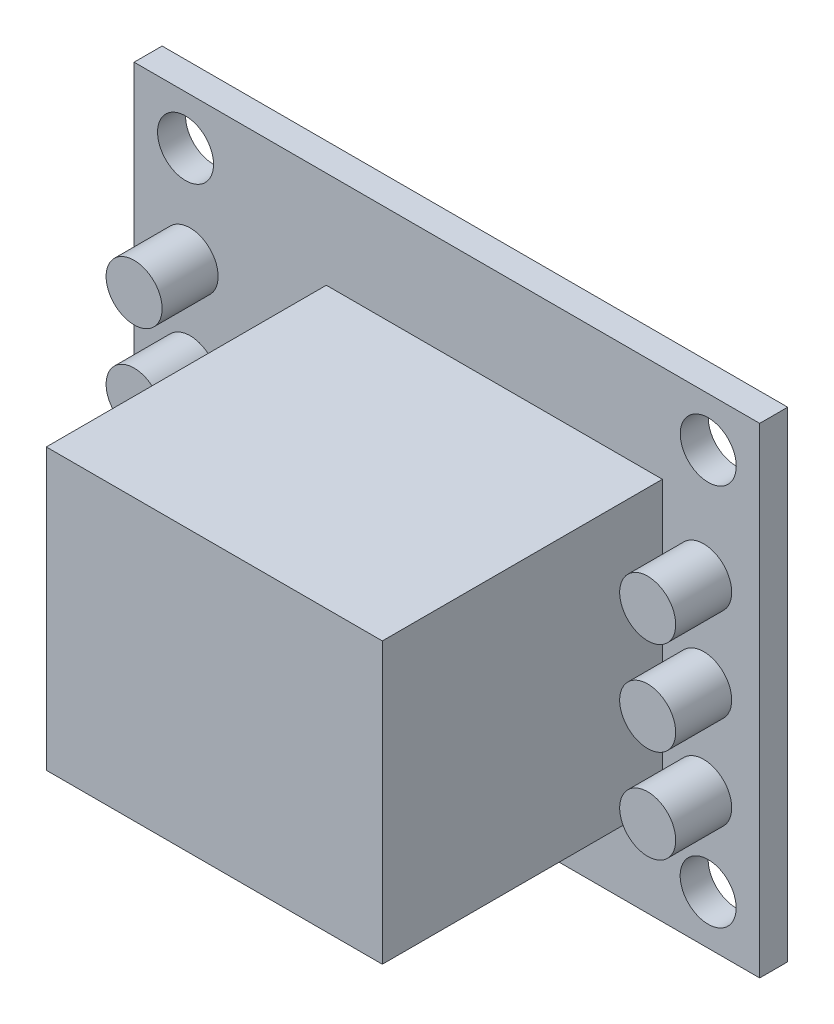
SolidWorks part; units mm, degrees
ref_plane "前基準面" through (0, 0, 0) normal (0, 0, 1) x (1, 0, 0)
ref_plane "上基準面" through (0, 0, 0) normal (0, 1, 0) x (1, 0, 0)
ref_plane "右基準面" through (0, 0, 0) normal (1, 0, 0) x (0, 0, -1)
sketch "草圖1" plane through (0, 0, 0) normal (0, 0, 1) x (1, 0, 0)
  line L1 (-14.2299, 12.6888) -> (19.2801, 12.6888)
  line L2 (-14.2299, 12.6888) -> (-14.2299, -13.0412)
  line L3 (-14.2299, -13.0412) -> (19.2801, -13.0412)
  line L4 (19.2801, 12.6888) -> (19.2801, -13.0412)
  circle A0 centre (-11.4749, 10.0738) radius 1.5
  circle A1 centre (-11.4799, -10.4262) radius 1.5
  circle A2 centre (16.5201, -10.4262) radius 1.5
  circle A3 centre (16.5251, 10.0738) radius 1.5
  dimension "D3" = 3
  dimension "D4" = 3
  dimension "D5" = 3
  dimension "D6" = 3
  dimension "D7" = 28
  dimension "D8" = 28
  dimension "D9" = 20.5
  dimension "D10" = 20.5
  dimension "D11" = 2.615
  dimension "D12" = 2.755
  dimension "D13" = 2.76
  dimension "D1" = 25.73
  dimension "D2" = 33.51
extrude "填料-伸長1" add sketch "草圖1" along normal blind 1.5
sketch "草圖2" plane through (0, 0, 1.5) normal (0, 0, 1) x (1, 0, 0)
  line L0 (19.2801, 12.6888) -> (-14.2299, 12.6888) construction
  line L1 (-3.9333, 7.4888) -> (14.0667, 7.4888)
  line L2 (-3.9333, 7.4888) -> (-3.9333, -7.5112)
  line L3 (-3.9333, -7.5112) -> (14.0667, -7.5112)
  line L4 (14.0667, 7.4888) -> (14.0667, -7.5112)
  dimension "D1" = 15
  dimension "D2" = 18
  dimension "D3" = 5.2
extrude "填料-伸長2" add sketch "草圖2" along normal blind 15
sketch "草圖3" plane through (0, 0, 1.5) normal (0, 0, 1) x (1, 0, 0)
  line L0 (-14.2299, 12.6888) -> (-14.2299, -13.0412) construction
  line L1 (19.2801, -13.0412) -> (19.2801, 12.6888) construction
  circle A0 centre (-11.2299, 5) radius 1.5
  circle A1 centre (-11.2299, 0) radius 1.5
  circle A2 centre (-11.2299, -5) radius 1.5
  circle A3 centre (16.2801, 4.1007) radius 1.5
  circle A4 centre (16.2801, -0.8993) radius 1.5
  circle A5 centre (16.2801, -5.8993) radius 1.5
  dimension "D1" = 3
  dimension "D5" = 3
  dimension "D6" = 3
  dimension "D7" = 3
  dimension "D8" = 5
  dimension "D9" = 5
  dimension "D10" = 5
  dimension "D11" = 5
  dimension "D2" = 3
  dimension "D3" = 3
  dimension "D4" = 3
extrude "填料-伸長3" add sketch "草圖3" along normal blind 3
